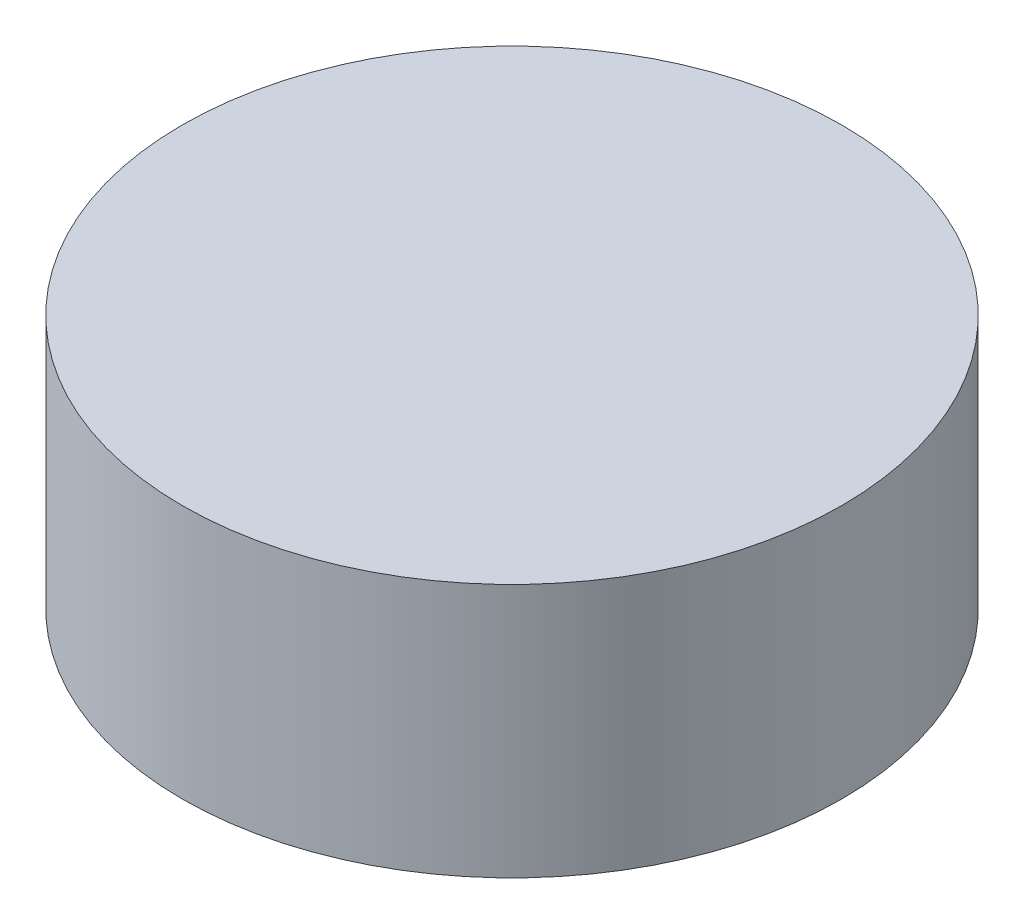
SolidWorks part; units mm, degrees
material "1060 Alloy"
ref_plane "Front Plane" through (0, 0, 0) normal (0, 0, 1) x (1, 0, 0)
ref_plane "Top Plane" through (0, 0, 0) normal (0, 1, 0) x (1, 0, 0)
ref_plane "Right Plane" through (0, 0, 0) normal (1, 0, 0) x (0, 0, -1)
sketch "Sketch1" plane through (0, 0, 0) normal (0, 1, 0) x (1, 0, 0)
  circle A0 centre (0, 0) radius 6.475
  dimension "D1" = 12.95
extrude "Boss-Extrude1" add sketch "Sketch1" along normal blind 4.9911
